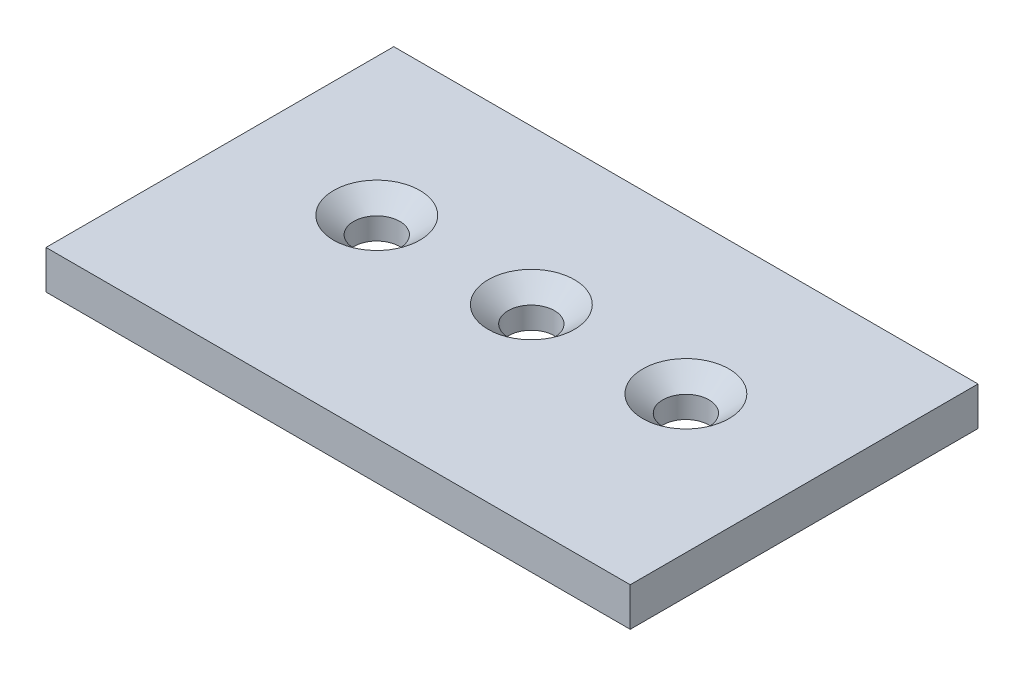
SolidWorks part; units mm, degrees
ref_plane "Front Plane" through (0, 0, 0) normal (0, 0, 1) x (1, 0, 0)
ref_plane "Top Plane" through (0, 0, 0) normal (0, 1, 0) x (1, 0, 0)
ref_plane "Right Plane" through (0, 0, 0) normal (1, 0, 0) x (0, 0, -1)
sketch "Sketch1" plane through (0, 0, 0) normal (0, 1, 0) x (1, 0, 0)
  line L1 (0, 0) -> (-48.006, 0)
  line L2 (0, 0) -> (0, 28.575)
  line L3 (0, 28.575) -> (-48.006, 28.575)
  line L4 (-48.006, 0) -> (-48.006, 28.575)
  dimension "D1" = 48.006
  dimension "D2" = 28.575
extrude "Boss-Extrude1" add sketch "Sketch1" along normal blind 3.175
hole_wizard "CSK for #6 Flat Head Machine Screw (100)1" positions "Sketch3" profile "Sketch2" countersink size "#6" standard "ANSI Inch" end condition through all
sketch "Sketch3" plane through (0, 3.175, 0) normal (0, 1, 0) x (1, 0, 0)
  line L0 (-48.006, 28.575) -> (-48.006, 0) construction
  line L1 (0, 28.575) -> (-48.006, 28.575) construction
  point P0 (-24.003, 15.875)
  dimension "D1" = 24.003
  dimension "D2" = 12.7
sketch "Sketch2" plane through (-24.003, 3.175, -15.875) normal (1, 0, 0) x (0, 0, 1)
  line L0 (0, 0) -> (0, 3.175)
  line L1 (0, 3.175) -> (1.8986, 3.175)
  line L2 (1.8986, 3.175) -> (1.8986, 1.38)
  line L3 (1.8986, 1.38) -> (3.5433, 0)
  line L5 (3.5433, 0) -> (0, 0)
  line L6 (-1.8986, 1.38) -> (-3.5433, 0) construction
  line L11 (0, -6.35) -> (0, 107.95) construction
  dimension "Thru Hole Dia." = 3.7973
  dimension "Thru Hole Depth" = 3.175
  dimension "Near C'Sink Dia." = 7.0866
  dimension "Near C'Sink Angle" = 100
pattern_linear "LPattern1" count 2 spacing 12.7 along (1, 0, 0) count 2 spacing 12.7 along (-1, 0, 0) of "CSK for #6 Flat Head Machine Screw (100)1"
